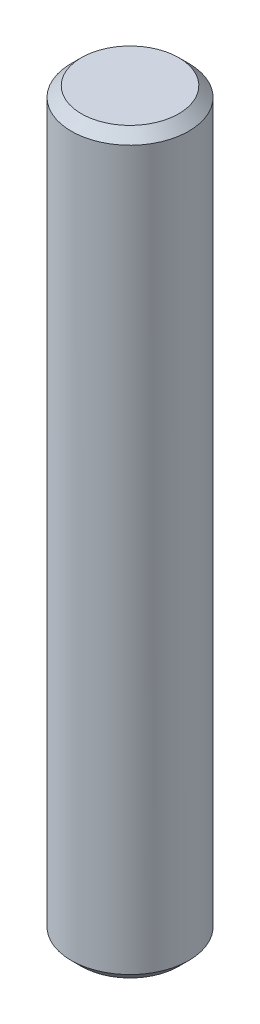
SolidWorks part; units mm, degrees
material "Acciaio al carbonio semplice"
ref_plane "Piano frontale" through (0, 0, 0) normal (0, 0, 1) x (1, 0, 0)
ref_plane "Piano superiore" through (0, 0, 0) normal (0, 1, 0) x (1, 0, 0)
ref_plane "Piano destro" through (0, 0, 0) normal (1, 0, 0) x (0, 0, -1)
sketch "Schizzo1" plane through (0, 0, 0) normal (0, 1, 0) x (1, 0, 0)
  circle A0 centre (0, 0) radius 3.5
  dimension "D1" = 7
extrude "Estrusione1" add sketch "Schizzo1" along normal blind 32 and the other way blind 12
chamfer "Smusso1" distance 0.6 angle 45 2 edges at (0, -12, 3.5) (0, 32, 3.5)
